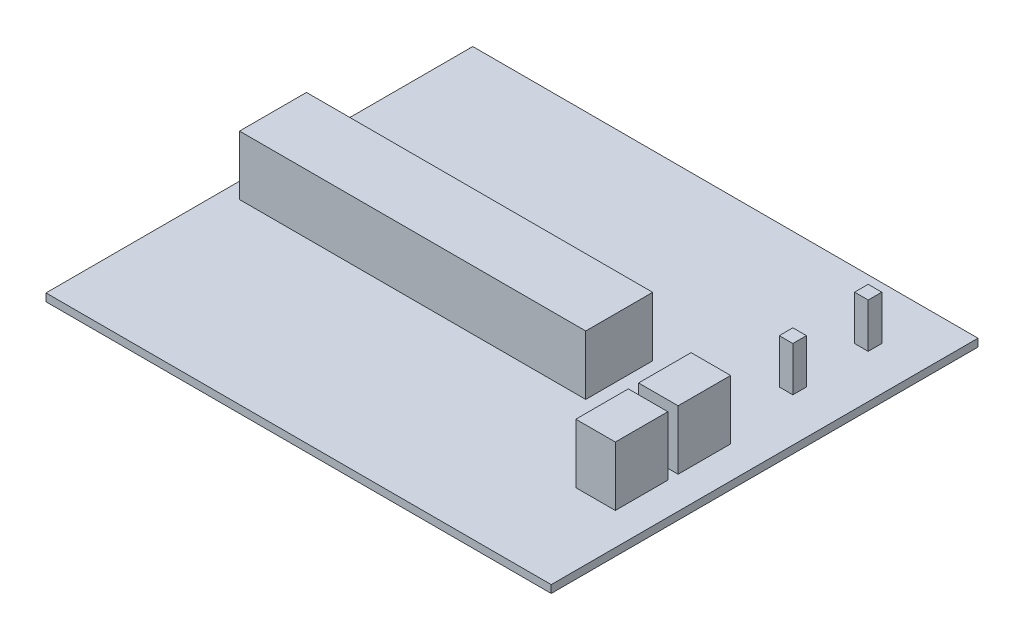
SolidWorks part; units mm, degrees
ref_plane "Front Plane" through (0, 0, 0) normal (0, 0, 1) x (1, 0, 0)
ref_plane "Top Plane" through (0, 0, 0) normal (0, 1, 0) x (1, 0, 0)
ref_plane "Right Plane" through (0, 0, 0) normal (1, 0, 0) x (0, 0, -1)
sketch "Sketch2" plane through (0, 0, 0) normal (0, 1, 0) x (1, 0, 0)
  line L0 (37.5994, 9.8296) -> (38.7847, 9.8296)
  line L1 (38.7847, 9.8296) -> (38.7847, 11.015)
  line L2 (38.7847, 11.015) -> (37.5994, 11.015)
  line L3 (37.5994, 11.015) -> (37.5994, 9.8296)
  line L4 (37.5994, 9.8296) -> (38.7847, 9.8296)
  line L5 (38.7847, 9.8296) -> (38.7847, 11.015)
  line L6 (38.7847, 11.015) -> (37.5994, 11.015)
  line L7 (37.5994, 11.015) -> (37.5994, 9.8296)
  line L8 (37.5994, 9.8296) -> (38.7847, 9.8296)
  line L9 (38.7847, 9.8296) -> (38.7847, 11.015)
  line L10 (38.7847, 11.015) -> (37.5994, 11.015)
  line L11 (37.5994, 11.015) -> (37.5994, 9.8296)
  line L12 (37.5994, 9.8296) -> (38.7847, 9.8296)
  line L13 (38.7847, 9.8296) -> (38.7847, 11.015)
  line L14 (38.7847, 11.015) -> (37.5994, 11.015)
  line L15 (37.5994, 11.015) -> (37.5994, 9.8296)
  line L16 (35.4827, 9.8296) -> (36.668, 9.8296)
  line L17 (36.668, 9.8296) -> (36.668, 11.015)
  line L18 (36.668, 11.015) -> (35.4827, 11.015)
  line L19 (35.4827, 11.015) -> (35.4827, 9.8296)
  line L20 (35.4827, 9.8296) -> (36.668, 9.8296)
  line L21 (36.668, 9.8296) -> (36.668, 11.015)
  line L22 (36.668, 11.015) -> (35.4827, 11.015)
  line L23 (35.4827, 11.015) -> (35.4827, 9.8296)
  line L24 (35.4827, 9.8296) -> (36.668, 9.8296)
  line L25 (36.668, 9.8296) -> (36.668, 11.015)
  line L26 (36.668, 11.015) -> (35.4827, 11.015)
  line L27 (35.4827, 11.015) -> (35.4827, 9.8296)
  line L28 (35.4827, 9.8296) -> (36.668, 9.8296)
  line L29 (36.668, 9.8296) -> (36.668, 11.015)
  line L30 (36.668, 11.015) -> (35.4827, 11.015)
  line L31 (35.4827, 11.015) -> (35.4827, 9.8296)
  line L32 (4.5794, 12.3696) -> (5.7647, 12.3696)
  line L33 (5.7647, 12.3696) -> (5.7647, 13.555)
  line L34 (5.7647, 13.555) -> (4.5794, 13.555)
  line L35 (4.5794, 13.555) -> (4.5794, 12.3696)
  line L36 (4.5794, 12.3696) -> (5.7647, 12.3696)
  line L37 (5.7647, 12.3696) -> (5.7647, 13.555)
  line L38 (5.7647, 13.555) -> (4.5794, 13.555)
  line L39 (4.5794, 13.555) -> (4.5794, 12.3696)
  line L40 (4.5794, 12.3696) -> (5.7647, 12.3696)
  line L41 (5.7647, 12.3696) -> (5.7647, 13.555)
  line L42 (5.7647, 13.555) -> (4.5794, 13.555)
  line L43 (4.5794, 13.555) -> (4.5794, 12.3696)
  line L44 (4.5794, 12.3696) -> (5.7647, 12.3696)
  line L45 (5.7647, 12.3696) -> (5.7647, 13.555)
  line L46 (5.7647, 13.555) -> (4.5794, 13.555)
  line L47 (4.5794, 13.555) -> (4.5794, 12.3696)
  line L48 (2.4627, 12.3696) -> (3.648, 12.3696)
  line L49 (3.648, 12.3696) -> (3.648, 13.555)
  line L50 (3.648, 13.555) -> (2.4627, 13.555)
  line L51 (2.4627, 13.555) -> (2.4627, 12.3696)
  line L52 (2.4627, 12.3696) -> (3.648, 12.3696)
  line L53 (3.648, 12.3696) -> (3.648, 13.555)
  line L54 (3.648, 13.555) -> (2.4627, 13.555)
  line L55 (2.4627, 13.555) -> (2.4627, 12.3696)
  line L56 (2.4627, 12.3696) -> (3.648, 12.3696)
  line L57 (3.648, 12.3696) -> (3.648, 13.555)
  line L58 (3.648, 13.555) -> (2.4627, 13.555)
  line L59 (2.4627, 13.555) -> (2.4627, 12.3696)
  line L60 (2.4627, 12.3696) -> (3.648, 12.3696)
  line L61 (3.648, 12.3696) -> (3.648, 13.555)
  line L62 (3.648, 13.555) -> (2.4627, 13.555)
  line L63 (2.4627, 13.555) -> (2.4627, 12.3696)
  line L64 (24.8994, 63.1696) -> (26.0847, 63.1696)
  line L65 (26.0847, 63.1696) -> (26.0847, 64.355)
  line L66 (26.0847, 64.355) -> (24.8994, 64.355)
  line L67 (24.8994, 64.355) -> (24.8994, 63.1696)
  line L68 (24.8994, 63.1696) -> (26.0847, 63.1696)
  line L69 (26.0847, 63.1696) -> (26.0847, 64.355)
  line L70 (26.0847, 64.355) -> (24.8994, 64.355)
  line L71 (24.8994, 64.355) -> (24.8994, 63.1696)
  line L72 (24.8994, 63.1696) -> (26.0847, 63.1696)
  line L73 (26.0847, 63.1696) -> (26.0847, 64.355)
  line L74 (26.0847, 64.355) -> (24.8994, 64.355)
  line L75 (24.8994, 64.355) -> (24.8994, 63.1696)
  line L76 (24.8994, 63.1696) -> (26.0847, 63.1696)
  line L77 (26.0847, 63.1696) -> (26.0847, 64.355)
  line L78 (26.0847, 64.355) -> (24.8994, 64.355)
  line L79 (24.8994, 64.355) -> (24.8994, 63.1696)
  line L80 (22.7827, 63.1696) -> (23.968, 63.1696)
  line L81 (23.968, 63.1696) -> (23.968, 64.355)
  line L82 (23.968, 64.355) -> (22.7827, 64.355)
  line L83 (22.7827, 64.355) -> (22.7827, 63.1696)
  line L84 (22.7827, 63.1696) -> (23.968, 63.1696)
  line L85 (23.968, 63.1696) -> (23.968, 64.355)
  line L86 (23.968, 64.355) -> (22.7827, 64.355)
  line L87 (22.7827, 64.355) -> (22.7827, 63.1696)
  line L88 (22.7827, 63.1696) -> (23.968, 63.1696)
  line L89 (23.968, 63.1696) -> (23.968, 64.355)
  line L90 (23.968, 64.355) -> (22.7827, 64.355)
  line L91 (22.7827, 64.355) -> (22.7827, 63.1696)
  line L92 (22.7827, 63.1696) -> (23.968, 63.1696)
  line L93 (23.968, 63.1696) -> (23.968, 64.355)
  line L94 (23.968, 64.355) -> (22.7827, 64.355)
  line L95 (22.7827, 64.355) -> (22.7827, 63.1696)
  line L96 (37.5994, 27.6096) -> (38.7847, 27.6096)
  line L97 (38.7847, 27.6096) -> (38.7847, 28.795)
  line L98 (38.7847, 28.795) -> (37.5994, 28.795)
  line L99 (37.5994, 28.795) -> (37.5994, 27.6096)
  line L100 (37.5994, 27.6096) -> (38.7847, 27.6096)
  line L101 (38.7847, 27.6096) -> (38.7847, 28.795)
  line L102 (38.7847, 28.795) -> (37.5994, 28.795)
  line L103 (37.5994, 28.795) -> (37.5994, 27.6096)
  line L104 (37.5994, 27.6096) -> (38.7847, 27.6096)
  line L105 (38.7847, 27.6096) -> (38.7847, 28.795)
  line L106 (38.7847, 28.795) -> (37.5994, 28.795)
  line L107 (37.5994, 28.795) -> (37.5994, 27.6096)
  line L108 (37.5994, 27.6096) -> (38.7847, 27.6096)
  line L109 (38.7847, 27.6096) -> (38.7847, 28.795)
  line L110 (38.7847, 28.795) -> (37.5994, 28.795)
  line L111 (37.5994, 28.795) -> (37.5994, 27.6096)
  line L112 (35.4827, 27.6096) -> (36.668, 27.6096)
  line L113 (36.668, 27.6096) -> (36.668, 28.795)
  line L114 (36.668, 28.795) -> (35.4827, 28.795)
  line L115 (35.4827, 28.795) -> (35.4827, 27.6096)
  line L116 (35.4827, 27.6096) -> (36.668, 27.6096)
  line L117 (36.668, 27.6096) -> (36.668, 28.795)
  line L118 (36.668, 28.795) -> (35.4827, 28.795)
  line L119 (35.4827, 28.795) -> (35.4827, 27.6096)
  line L120 (35.4827, 27.6096) -> (36.668, 27.6096)
  line L121 (36.668, 27.6096) -> (36.668, 28.795)
  line L122 (36.668, 28.795) -> (35.4827, 28.795)
  line L123 (35.4827, 28.795) -> (35.4827, 27.6096)
  line L124 (35.4827, 27.6096) -> (36.668, 27.6096)
  line L125 (36.668, 27.6096) -> (36.668, 28.795)
  line L126 (36.668, 28.795) -> (35.4827, 28.795)
  line L127 (35.4827, 28.795) -> (35.4827, 27.6096)
  line L128 (5.3837, 27.6096) -> (6.569, 27.6096)
  line L129 (6.569, 27.6096) -> (6.569, 28.795)
  line L130 (6.569, 28.795) -> (5.3837, 28.795)
  line L131 (5.3837, 28.795) -> (5.3837, 27.6096)
  line L132 (5.3837, 27.6096) -> (6.569, 27.6096)
  line L133 (6.569, 27.6096) -> (6.569, 28.795)
  line L134 (6.569, 28.795) -> (5.3837, 28.795)
  line L135 (5.3837, 28.795) -> (5.3837, 27.6096)
  line L136 (5.3837, 27.6096) -> (6.569, 27.6096)
  line L137 (6.569, 27.6096) -> (6.569, 28.795)
  line L138 (6.569, 28.795) -> (5.3837, 28.795)
  line L139 (5.3837, 28.795) -> (5.3837, 27.6096)
  line L140 (5.3837, 27.6096) -> (6.569, 27.6096)
  line L141 (6.569, 27.6096) -> (6.569, 28.795)
  line L142 (6.569, 28.795) -> (5.3837, 28.795)
  line L143 (5.3837, 28.795) -> (5.3837, 27.6096)
  line L144 (7.5427, 27.6096) -> (8.728, 27.6096)
  line L145 (8.728, 27.6096) -> (8.728, 28.795)
  line L146 (8.728, 28.795) -> (7.5427, 28.795)
  line L147 (7.5427, 28.795) -> (7.5427, 27.6096)
  line L148 (7.5427, 27.6096) -> (8.728, 27.6096)
  line L149 (8.728, 27.6096) -> (8.728, 28.795)
  line L150 (8.728, 28.795) -> (7.5427, 28.795)
  line L151 (7.5427, 28.795) -> (7.5427, 27.6096)
  line L152 (7.5427, 27.6096) -> (8.728, 27.6096)
  line L153 (8.728, 27.6096) -> (8.728, 28.795)
  line L154 (8.728, 28.795) -> (7.5427, 28.795)
  line L155 (7.5427, 28.795) -> (7.5427, 27.6096)
  line L156 (7.5427, 27.6096) -> (8.728, 27.6096)
  line L157 (8.728, 27.6096) -> (8.728, 28.795)
  line L158 (8.728, 28.795) -> (7.5427, 28.795)
  line L159 (7.5427, 28.795) -> (7.5427, 27.6096)
  line L160 (24.8994, 80.9496) -> (26.0847, 80.9496)
  line L161 (26.0847, 80.9496) -> (26.0847, 82.135)
  line L162 (26.0847, 82.135) -> (24.8994, 82.135)
  line L163 (24.8994, 82.135) -> (24.8994, 80.9496)
  line L164 (24.8994, 80.9496) -> (26.0847, 80.9496)
  line L165 (26.0847, 80.9496) -> (26.0847, 82.135)
  line L166 (26.0847, 82.135) -> (24.8994, 82.135)
  line L167 (24.8994, 82.135) -> (24.8994, 80.9496)
  line L168 (24.8994, 80.9496) -> (26.0847, 80.9496)
  line L169 (26.0847, 80.9496) -> (26.0847, 82.135)
  line L170 (26.0847, 82.135) -> (24.8994, 82.135)
  line L171 (24.8994, 82.135) -> (24.8994, 80.9496)
  line L172 (24.8994, 80.9496) -> (26.0847, 80.9496)
  line L173 (26.0847, 80.9496) -> (26.0847, 82.135)
  line L174 (26.0847, 82.135) -> (24.8994, 82.135)
  line L175 (24.8994, 82.135) -> (24.8994, 80.9496)
  line L176 (22.7827, 80.9496) -> (23.968, 80.9496)
  line L177 (23.968, 80.9496) -> (23.968, 82.135)
  line L178 (23.968, 82.135) -> (22.7827, 82.135)
  line L179 (22.7827, 82.135) -> (22.7827, 80.9496)
  line L180 (22.7827, 80.9496) -> (23.968, 80.9496)
  line L181 (23.968, 80.9496) -> (23.968, 82.135)
  line L182 (23.968, 82.135) -> (22.7827, 82.135)
  line L183 (22.7827, 82.135) -> (22.7827, 80.9496)
  line L184 (22.7827, 80.9496) -> (23.968, 80.9496)
  line L185 (23.968, 80.9496) -> (23.968, 82.135)
  line L186 (23.968, 82.135) -> (22.7827, 82.135)
  line L187 (22.7827, 82.135) -> (22.7827, 80.9496)
  line L188 (22.7827, 80.9496) -> (23.968, 80.9496)
  line L189 (23.968, 80.9496) -> (23.968, 82.135)
  line L190 (23.968, 82.135) -> (22.7827, 82.135)
  line L191 (22.7827, 82.135) -> (22.7827, 80.9496)
  line L192 (57.9194, 63.1696) -> (59.1047, 63.1696)
  line L193 (59.1047, 63.1696) -> (59.1047, 64.355)
  line L194 (59.1047, 64.355) -> (57.9194, 64.355)
  line L195 (57.9194, 64.355) -> (57.9194, 63.1696)
  line L196 (57.9194, 63.1696) -> (59.1047, 63.1696)
  line L197 (59.1047, 63.1696) -> (59.1047, 64.355)
  line L198 (59.1047, 64.355) -> (57.9194, 64.355)
  line L199 (57.9194, 64.355) -> (57.9194, 63.1696)
  line L200 (57.9194, 63.1696) -> (59.1047, 63.1696)
  line L201 (59.1047, 63.1696) -> (59.1047, 64.355)
  line L202 (59.1047, 64.355) -> (57.9194, 64.355)
  line L203 (57.9194, 64.355) -> (57.9194, 63.1696)
  line L204 (57.9194, 63.1696) -> (59.1047, 63.1696)
  line L205 (59.1047, 63.1696) -> (59.1047, 64.355)
  line L206 (59.1047, 64.355) -> (57.9194, 64.355)
  line L207 (57.9194, 64.355) -> (57.9194, 63.1696)
  line L208 (55.8027, 63.1696) -> (56.988, 63.1696)
  line L209 (56.988, 63.1696) -> (56.988, 64.355)
  line L210 (56.988, 64.355) -> (55.8027, 64.355)
  line L211 (55.8027, 64.355) -> (55.8027, 63.1696)
  line L212 (55.8027, 63.1696) -> (56.988, 63.1696)
  line L213 (56.988, 63.1696) -> (56.988, 64.355)
  line L214 (56.988, 64.355) -> (55.8027, 64.355)
  line L215 (55.8027, 64.355) -> (55.8027, 63.1696)
  line L216 (55.8027, 63.1696) -> (56.988, 63.1696)
  line L217 (56.988, 63.1696) -> (56.988, 64.355)
  line L218 (56.988, 64.355) -> (55.8027, 64.355)
  line L219 (55.8027, 64.355) -> (55.8027, 63.1696)
  line L220 (55.8027, 63.1696) -> (56.988, 63.1696)
  line L221 (56.988, 63.1696) -> (56.988, 64.355)
  line L222 (56.988, 64.355) -> (55.8027, 64.355)
  line L223 (55.8027, 64.355) -> (55.8027, 63.1696)
  line L224 (55.3794, 80.9496) -> (56.5647, 80.9496)
  line L225 (56.5647, 80.9496) -> (56.5647, 82.135)
  line L226 (56.5647, 82.135) -> (55.3794, 82.135)
  line L227 (55.3794, 82.135) -> (55.3794, 80.9496)
  line L228 (55.3794, 80.9496) -> (56.5647, 80.9496)
  line L229 (56.5647, 80.9496) -> (56.5647, 82.135)
  line L230 (56.5647, 82.135) -> (55.3794, 82.135)
  line L231 (55.3794, 82.135) -> (55.3794, 80.9496)
  line L232 (55.3794, 80.9496) -> (56.5647, 80.9496)
  line L233 (56.5647, 80.9496) -> (56.5647, 82.135)
  line L234 (56.5647, 82.135) -> (55.3794, 82.135)
  line L235 (55.3794, 82.135) -> (55.3794, 80.9496)
  line L236 (55.3794, 80.9496) -> (56.5647, 80.9496)
  line L237 (56.5647, 80.9496) -> (56.5647, 82.135)
  line L238 (56.5647, 82.135) -> (55.3794, 82.135)
  line L239 (55.3794, 82.135) -> (55.3794, 80.9496)
  line L240 (53.2627, 80.9496) -> (54.448, 80.9496)
  line L241 (54.448, 80.9496) -> (54.448, 82.135)
  line L242 (54.448, 82.135) -> (53.2627, 82.135)
  line L243 (53.2627, 82.135) -> (53.2627, 80.9496)
  line L244 (53.2627, 80.9496) -> (54.448, 80.9496)
  line L245 (54.448, 80.9496) -> (54.448, 82.135)
  line L246 (54.448, 82.135) -> (53.2627, 82.135)
  line L247 (53.2627, 82.135) -> (53.2627, 80.9496)
  line L248 (53.2627, 80.9496) -> (54.448, 80.9496)
  line L249 (54.448, 80.9496) -> (54.448, 82.135)
  line L250 (54.448, 82.135) -> (53.2627, 82.135)
  line L251 (53.2627, 82.135) -> (53.2627, 80.9496)
  line L252 (53.2627, 80.9496) -> (54.448, 80.9496)
  line L253 (54.448, 80.9496) -> (54.448, 82.135)
  line L254 (54.448, 82.135) -> (53.2627, 82.135)
  line L255 (53.2627, 82.135) -> (53.2627, 80.9496)
  line L256 (90.5584, 57.3276) -> (93.31, 57.3276)
  line L257 (93.31, 57.3276) -> (93.31, 60.0793)
  line L258 (93.31, 60.0793) -> (90.5584, 60.0793)
  line L259 (90.5584, 60.0793) -> (90.5584, 57.3276)
  line L260 (93.31, 19.1006) -> (93.31, 29.7263)
  line L261 (93.31, 29.7263) -> (82.9384, 29.7263)
  line L262 (82.9384, 29.7263) -> (82.9384, 19.1006)
  line L263 (82.9384, 19.1006) -> (93.31, 19.1006)
  line L264 (49.7914, 16.1796) -> (49.7914, 7.713)
  line L265 (49.7914, 7.713) -> (59.6974, 7.713)
  line L266 (59.6974, 7.713) -> (59.6974, 16.1796)
  line L267 (59.6974, 16.1796) -> (49.7914, 16.1796)
  line L268 (65.0314, 82.2196) -> (65.0314, 73.753)
  line L269 (65.0314, 73.753) -> (74.9374, 73.753)
  line L270 (74.9374, 73.753) -> (74.9374, 82.2196)
  line L271 (74.9374, 82.2196) -> (65.0314, 82.2196)
  line L272 (35.017, 27.1863) -> (39.2504, 27.1863)
  line L273 (39.2504, 27.1863) -> (39.2504, 29.2183)
  line L274 (39.2504, 29.2183) -> (35.017, 29.2183)
  line L275 (35.017, 29.2183) -> (35.017, 27.1863)
  line L276 (90.5584, 72.5676) -> (93.31, 72.5676)
  line L277 (93.31, 72.5676) -> (93.31, 75.3193)
  line L278 (93.31, 75.3193) -> (90.5584, 75.3193)
  line L279 (90.5584, 75.3193) -> (90.5584, 72.5676)
  line L280 (-0.1196, 9.1523) -> (-0.1196, -0.3727)
  line L281 (-0.1196, -0.3727) -> (102.1154, -0.3727)
  line L282 (102.1154, -0.3727) -> (102.1154, 85.9873)
  line L283 (102.1154, 85.9873) -> (-0.1196, 85.9873)
  line L284 (-0.1196, 85.9873) -> (-0.1196, 9.1523)
  line L285 (35.017, 9.4063) -> (39.2504, 9.4063)
  line L286 (39.2504, 9.4063) -> (39.2504, 11.4383)
  line L287 (39.2504, 11.4383) -> (35.017, 11.4383)
  line L288 (35.017, 11.4383) -> (35.017, 9.4063)
  line L289 (1.997, 11.9463) -> (6.2304, 11.9463)
  line L290 (6.2304, 11.9463) -> (6.2304, 13.9783)
  line L291 (6.2304, 13.9783) -> (1.997, 13.9783)
  line L292 (1.997, 13.9783) -> (1.997, 11.9463)
  line L293 (65.0314, 64.4396) -> (65.0314, 55.973)
  line L294 (65.0314, 55.973) -> (74.9374, 55.973)
  line L295 (74.9374, 55.973) -> (74.9374, 64.4396)
  line L296 (74.9374, 64.4396) -> (65.0314, 64.4396)
  line L297 (4.0714, 82.2196) -> (4.0714, 73.753)
  line L298 (4.0714, 73.753) -> (13.9774, 73.753)
  line L299 (13.9774, 73.753) -> (13.9774, 82.2196)
  line L300 (13.9774, 82.2196) -> (4.0714, 82.2196)
  line L301 (16.7714, 31.4196) -> (16.7714, 22.953)
  line L302 (16.7714, 22.953) -> (26.6774, 22.953)
  line L303 (26.6774, 22.953) -> (26.6774, 31.4196)
  line L304 (26.6774, 31.4196) -> (16.7714, 31.4196)
  line L305 (9.1514, 29.2183) -> (4.9604, 29.2183)
  line L306 (4.9604, 29.2183) -> (4.9604, 27.1863)
  line L307 (4.9604, 27.1863) -> (9.1514, 27.1863)
  line L308 (9.1514, 27.1863) -> (9.1514, 29.2183)
  line L309 (52.797, 80.5263) -> (57.0304, 80.5263)
  line L310 (57.0304, 80.5263) -> (57.0304, 82.5583)
  line L311 (57.0304, 82.5583) -> (52.797, 82.5583)
  line L312 (52.797, 82.5583) -> (52.797, 80.5263)
  line L313 (22.317, 62.7463) -> (26.5504, 62.7463)
  line L314 (26.5504, 62.7463) -> (26.5504, 64.7783)
  line L315 (26.5504, 64.7783) -> (22.317, 64.7783)
  line L316 (22.317, 64.7783) -> (22.317, 62.7463)
  line L317 (34.5514, 64.4396) -> (34.5514, 55.973)
  line L318 (34.5514, 55.973) -> (44.4574, 55.973)
  line L319 (44.4574, 55.973) -> (44.4574, 64.4396)
  line L320 (44.4574, 64.4396) -> (34.5514, 64.4396)
  line L321 (3.0977, 35.5683) -> (73.1594, 35.5683)
  line L322 (73.1594, 35.5683) -> (73.1594, 49.115)
  line L323 (73.1594, 49.115) -> (3.0977, 49.115)
  line L324 (3.0977, 49.115) -> (3.0977, 35.5683)
  line L325 (55.337, 62.7463) -> (59.5704, 62.7463)
  line L326 (59.5704, 62.7463) -> (59.5704, 64.7783)
  line L327 (59.5704, 64.7783) -> (55.337, 64.7783)
  line L328 (55.337, 64.7783) -> (55.337, 62.7463)
  line L329 (34.5514, 82.2196) -> (34.5514, 73.753)
  line L330 (34.5514, 73.753) -> (44.4574, 73.753)
  line L331 (44.4574, 73.753) -> (44.4574, 82.2196)
  line L332 (44.4574, 82.2196) -> (34.5514, 82.2196)
  line L333 (16.7714, 16.1796) -> (16.7714, 7.713)
  line L334 (16.7714, 7.713) -> (26.6774, 7.713)
  line L335 (26.6774, 7.713) -> (26.6774, 16.1796)
  line L336 (26.6774, 16.1796) -> (16.7714, 16.1796)
  line L337 (22.317, 80.5263) -> (26.5504, 80.5263)
  line L338 (26.5504, 80.5263) -> (26.5504, 82.5583)
  line L339 (26.5504, 82.5583) -> (22.317, 82.5583)
  line L340 (22.317, 82.5583) -> (22.317, 80.5263)
  line L341 (49.7914, 31.4196) -> (49.7914, 22.953)
  line L342 (49.7914, 22.953) -> (59.6974, 22.953)
  line L343 (59.6974, 22.953) -> (59.6974, 31.4196)
  line L344 (59.6974, 31.4196) -> (49.7914, 31.4196)
  line L345 (4.0714, 64.4396) -> (4.0714, 55.973)
  line L346 (4.0714, 55.973) -> (13.9774, 55.973)
  line L347 (13.9774, 55.973) -> (13.9774, 64.4396)
  line L348 (13.9774, 64.4396) -> (4.0714, 64.4396)
  line L349 (93.31, 31.8006) -> (93.31, 42.4263)
  line L350 (93.31, 42.4263) -> (82.9384, 42.4263)
  line L351 (82.9384, 42.4263) -> (82.9384, 31.8006)
  line L352 (82.9384, 31.8006) -> (93.31, 31.8006)
sketch "Sketch3" plane through (0, 0, 0) normal (0, 1, 0) x (1, 0, 0)
  line L0 (-0.1196, 85.9873) -> (-0.1196, 9.1523) construction
  line L1 (102.1154, 85.9873) -> (-0.1196, 85.9873) construction
  line L2 (102.1154, -0.3727) -> (102.1154, 85.9873) construction
  line L3 (-0.1196, -0.3727) -> (102.1154, -0.3727) construction
  line L4 (-0.1196, 85.9873) -> (-0.1196, -0.3727)
  line L5 (102.1154, 85.9873) -> (-0.1196, 85.9873)
  line L6 (102.1154, -0.3727) -> (102.1154, 85.9873)
  line L7 (-0.1196, -0.3727) -> (102.1154, -0.3727)
extrude "Boss-Extrude1" add sketch "Sketch3" along normal blind 1.56
sketch "Sketch4" plane through (0, 1.56, 0) normal (0, 1, 0) x (1, 0, 0)
  line L0 (3.0977, 35.5683) -> (73.1594, 35.5683) construction
  line L1 (3.0977, 49.115) -> (3.0977, 35.5683) construction
  line L2 (73.1594, 49.115) -> (3.0977, 49.115) construction
  line L3 (73.1594, 35.5683) -> (73.1594, 49.115) construction
  line L4 (3.0977, 35.5683) -> (73.1594, 35.5683)
  line L5 (3.0977, 49.115) -> (3.0977, 35.5683)
  line L6 (73.1594, 49.115) -> (3.0977, 49.115)
  line L7 (73.1594, 35.5683) -> (73.1594, 49.115)
extrude "Boss-Extrude2" add sketch "Sketch4" along normal blind 12
sketch "Sketch5" plane through (0, 1.56, 0) normal (0, 1, 0) x (1, 0, 0)
  line L0 (93.31, 29.7263) -> (82.9384, 29.7263) construction
  line L1 (93.31, 19.1006) -> (93.31, 29.7263) construction
  line L2 (82.9384, 19.1006) -> (93.31, 19.1006) construction
  line L3 (82.9384, 29.7263) -> (82.9384, 19.1006) construction
  line L4 (82.9384, 42.4263) -> (82.9384, 31.8006) construction
  line L5 (82.9384, 31.8006) -> (93.31, 31.8006) construction
  line L6 (93.31, 31.8006) -> (93.31, 42.4263) construction
  line L7 (93.31, 42.4263) -> (82.9384, 42.4263) construction
  line L8 (93.31, 29.7263) -> (82.9384, 29.7263) construction
  line L9 (93.31, 19.1006) -> (93.31, 29.7263) construction
  line L10 (82.9384, 19.1006) -> (93.31, 19.1006) construction
  line L11 (82.9384, 29.7263) -> (82.9384, 19.1006) construction
  line L12 (82.9384, 42.4263) -> (82.9384, 31.8006) construction
  line L13 (82.9384, 31.8006) -> (93.31, 31.8006) construction
  line L14 (93.31, 31.8006) -> (93.31, 42.4263) construction
  line L15 (93.31, 42.4263) -> (82.9384, 42.4263) construction
  line L16 (87.6154, 42.4263) -> (95.6154, 42.4263)
  line L17 (95.6154, 42.4263) -> (95.6154, 31.8006)
  line L18 (95.6154, 31.8006) -> (87.6154, 31.8006)
  line L19 (87.6154, 31.8006) -> (87.6154, 42.4263)
  line L20 (102.1154, -0.3727) -> (102.1154, 85.9873) construction
  line L21 (87.6154, 29.7263) -> (87.6154, 19.1006)
  line L22 (87.6154, 19.1006) -> (95.6154, 19.1006)
  line L23 (95.6154, 19.1006) -> (95.6154, 29.7263)
  line L24 (95.6154, 29.7263) -> (87.6154, 29.7263)
  dimension "D1" = 6.5
  dimension "D2" = 8
extrude "Boss-Extrude3" add sketch "Sketch5" along normal blind 12
sketch "Sketch6" plane through (0, 1.56, 0) normal (0, 1, 0) x (1, 0, 0)
  line L0 (93.31, 60.0793) -> (90.5584, 60.0793) construction
  line L1 (90.5584, 57.3276) -> (93.31, 57.3276) construction
  line L2 (90.5584, 60.0793) -> (90.5584, 57.3276) construction
  line L3 (93.31, 57.3276) -> (93.31, 60.0793) construction
  line L4 (90.5584, 72.5676) -> (93.31, 72.5676) construction
  line L5 (90.5584, 75.3193) -> (90.5584, 72.5676) construction
  line L6 (93.31, 75.3193) -> (90.5584, 75.3193) construction
  line L7 (93.31, 72.5676) -> (93.31, 75.3193) construction
  line L8 (93.31, 60.0793) -> (90.5584, 60.0793)
  line L9 (90.5584, 57.3276) -> (93.31, 57.3276)
  line L10 (90.5584, 60.0793) -> (90.5584, 57.3276)
  line L11 (93.31, 57.3276) -> (93.31, 60.0793)
  line L12 (90.5584, 72.5676) -> (93.31, 72.5676)
  line L13 (90.5584, 75.3193) -> (90.5584, 72.5676)
  line L14 (93.31, 75.3193) -> (90.5584, 75.3193)
  line L15 (93.31, 72.5676) -> (93.31, 75.3193)
extrude "Boss-Extrude4" add sketch "Sketch6" along normal blind 9
